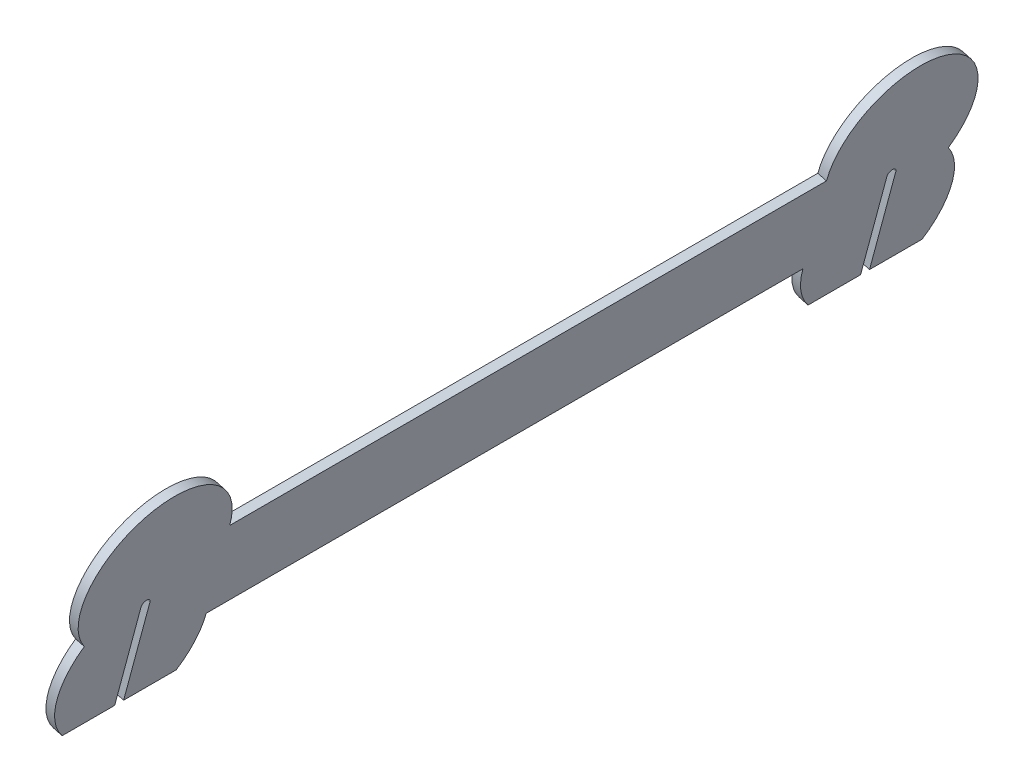
SolidWorks part; units mm, degrees
ref_plane "Plano frontal" through (0, 0, 0) normal (0, 0, 1) x (1, 0, 0)
ref_plane "Plano superior" through (0, 0, 0) normal (0, 1, 0) x (1, 0, 0)
ref_plane "Plano direito" through (0, 0, 0) normal (1, 0, 0) x (0, 0, -1)
sketch "Esboço1" plane through (0, 0, 0) normal (0, 0, 1) x (1, 0, 0)
  line L0 (-200, 0) -> (200, 0)
  line L1 (150, 26) -> (144.1525, 26)
  line L2 (0, 0) -> (0, 26) construction
  line L3 (150, 26) -> (-150, 26) construction
  line L4 (150, 20) -> (150, 26) construction
  line L5 (144.1525, 26) -> (138.2626, 30.3047)
  line L6 (150, 20) -> (-150, 20)
  line L7 (138.2626, 30.3047) -> (153.1541, 34.1943)
  line L8 (139.0472, 52.7422) -> (160.0854, 40.2451)
  line L9 (139.0472, 52.7422) -> (150.7846, 58.3876)
  line L10 (150.7846, 58.3876) -> (140, 61)
  line L11 (160.0854, 40.2451) -> (137.5975, 43.4375)
  line L12 (137.5975, 43.4375) -> (153.1541, 34.1943)
  line L13 (140, 61) -> (200, 61)
  line L14 (289.6201, 30.5) -> (200, 30.5) construction
  line L15 (200, 30.5) -> (200, 61) construction
  line L16 (250, 61) -> (262.9328, 109.2659) construction
  line L17 (210, -30) -> (290, -30)
  line L18 (260.0199, 109.9857) -> (240.6084, 37.5413)
  line L19 (246.404, 35.9884) -> (265.8154, 108.4328)
  line L20 (240.6084, 37.5413) -> (246.404, 35.9884) construction
  line L21 (243.5062, 36.7648) -> (250, 61) construction
  line L22 (-243.5062, 36.7648) -> (-250, 61) construction
  line L23 (-240.6084, 37.5413) -> (-246.404, 35.9884) construction
  line L24 (-250, 61) -> (-262.9328, 109.2659) construction
  line L25 (-200, 30.5) -> (-200, 61) construction
  line L26 (-289.6201, 30.5) -> (-200, 30.5) construction
  line L27 (-150, 20) -> (-150, 26) construction
  line L28 (-246.404, 35.9884) -> (-265.8154, 108.4328)
  line L29 (-260.0199, 109.9857) -> (-240.6084, 37.5413)
  line L30 (-210, -30) -> (-290, -30)
  line L31 (-140, 61) -> (-200, 61)
  line L32 (-137.5975, 43.4375) -> (-153.1541, 34.1943)
  line L33 (-160.0854, 40.2451) -> (-137.5975, 43.4375)
  line L34 (-150.7846, 58.3876) -> (-140, 61)
  line L35 (-139.0472, 52.7422) -> (-150.7846, 58.3876)
  line L36 (-139.0472, 52.7422) -> (-160.0854, 40.2451)
  line L37 (-138.2626, 30.3047) -> (-153.1541, 34.1943)
  line L38 (-144.1525, 26) -> (-138.2626, 30.3047)
  line L39 (-150, 26) -> (-144.1525, 26)
  arc A0 (150, 20) -> (150, 26) centre (150, 23) ccw
  arc A1 (200, 61) -> (260.0199, 109.9857) centre (250, 61) cw
  arc A2 (200, 0) -> (210, -30) centre (250, 0) ccw
  arc A3 (290, -30) -> (289.6201, 30.5) centre (250, 0) ccw
  arc A4 (240.6084, 37.5413) -> (246.404, 35.9884) centre (243.5062, 36.7648) ccw
  arc A5 (265.8154, 108.4328) -> (289.6201, 30.5) centre (250, 61) cw
  arc A6 (-265.8154, 108.4328) -> (-289.6201, 30.5) centre (-250, 61) ccw
  arc A7 (-240.6084, 37.5413) -> (-246.404, 35.9884) centre (-243.5062, 36.7648) cw
  arc A8 (-290, -30) -> (-289.6201, 30.5) centre (-250, 0) cw
  arc A9 (-200, 0) -> (-210, -30) centre (-250, 0) cw
  arc A10 (-200, 61) -> (-260.0199, 109.9857) centre (-250, 61) ccw
  arc A11 (-150, 20) -> (-150, 26) centre (-150, 23) cw
  point P45 (0, 20)
  point P54 (0, 20)
  dimension "D7" = 30
  dimension "D9" = 15
  dimension "D10" = 6
  dimension "D11" = 75
  dimension "D1" = 3
  dimension "D6" = 50
  dimension "D2" = 200
  dimension "D3" = 20
  dimension "D4" = 150
  dimension "D5" = 61
  dimension "D8" = 140
extrude "Ressalto-extrusão2" add sketch "Esboço1" along normal blind 6
sketch "Esboço4" plane through (215.1054, -57.6373, 0) normal (0.9659, -0.2588, 0) x (0, 0, -1)
  line L0 (-6, 173.5362) -> (0, 173.5362) construction
  line L1 (-3, 123.5362) -> (-3, 173.5362) construction
  line L2 (247, 62.5362) -> (247, 123.5362)
  line L9 (247, 123.5362) -> (47, 123.5362)
  line L27 (-41.2176, 30.2962) -> (35.2176, 30.2962)
  line L28 (47, 62.5362) -> (247, 62.5362)
  line L29 (247, 62.5362) -> (247, 123.5362) construction
  arc A1 (47, 123.5362) -> (-3, 173.5362) centre (-3, 123.5362) ccw
  arc A3 (-3, 173.5362) -> (-42.6201, 93.0362) centre (-3, 123.5362) ccw
  arc A4 (-42.6201, 93.0362) -> (-41.2176, 30.2962) centre (-3, 62.5362) ccw
  arc A5 (35.2176, 30.2962) -> (47, 62.5362) centre (-3, 62.5362) ccw
  dimension "D4" = 50
  dimension "D9" = 50
  dimension "D10" = 50
  dimension "D1" = 61
  dimension "D2" = 123.5362
  dimension "D3" = 200
  dimension "D5" = 30.5
  dimension "D6" = 61
  dimension "D7" = 32.24
extrude "Ressalto-extrusão3" add sketch "Esboço4" along normal blind 6 separate body
combine bodies "Combinar1" operation type subtract main body 106 bodies to subtract 102
sketch "Esboço6" plane through (220.901, -59.1902, 0) normal (0.9659, -0.2588, 0) x (0, 0, -1)
  line L3 (0, 98.5362) -> (0, 30.2962) construction
  line L5 (-6, 98.5362) -> (-6, 92.5976)
  line L6 (-6, 92.5976) -> (0, 92.5976)
  line L7 (0, 98.5362) -> (0, 92.5976)
  line L8 (0, 98.5362) -> (0, 95.5362) construction
  arc A0 (0, 98.5362) -> (-6, 98.5362) centre (-3, 98.5362) ccw
  dimension "D1" = 3
extrude "Corte-extrusão1" cut sketch "Esboço6" against normal through all
mirror "Espelhar2" about plane through (237.0865, 1.2151, -247) normal (0, 0, 1) of bodies 108
